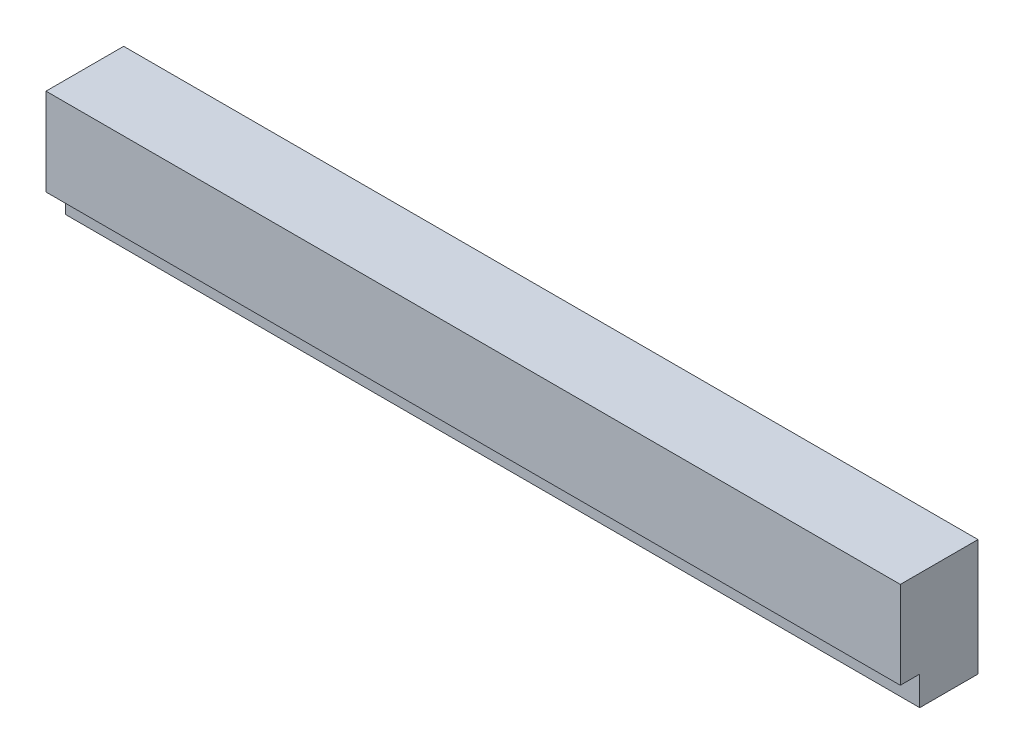
SolidWorks part; units mm, degrees
ref_plane "Front Plane" through (0, 0, 0) normal (0, 0, 1) x (1, 0, 0)
ref_plane "Top Plane" through (0, 0, 0) normal (0, 1, 0) x (1, 0, 0)
ref_plane "Right Plane" through (0, 0, 0) normal (1, 0, 0) x (0, 0, -1)
sketch "Sketch1" plane through (0, 0, 0) normal (0, 1, 0) x (1, 0, 0)
  line L1 (-440, 40) -> (440, 40)
  line L2 (-440, 40) -> (-440, -40)
  line L3 (-440, -40) -> (440, -40)
  line L4 (440, 40) -> (440, -40)
  line L5 (0, -40) -> (0, 40) construction
  line L6 (-440, 0) -> (440, 0) construction
  point P0 (0, 0)
extrude "Boss-Extrude1" add sketch "Sketch1" along normal blind 120
sketch "Sketch2" plane through (440, 0, 0) normal (1, 0, 0) x (0, 0, -1)
  line L2 (-40, 0) -> (-20, 0)
  line L3 (-40, 0) -> (-40, 30)
  line L4 (-40, 30) -> (-20, 30)
  line L5 (-20, 0) -> (-20, 30)
extrude "Cut-Extrude1" cut sketch "Sketch2" against normal blind 1067
